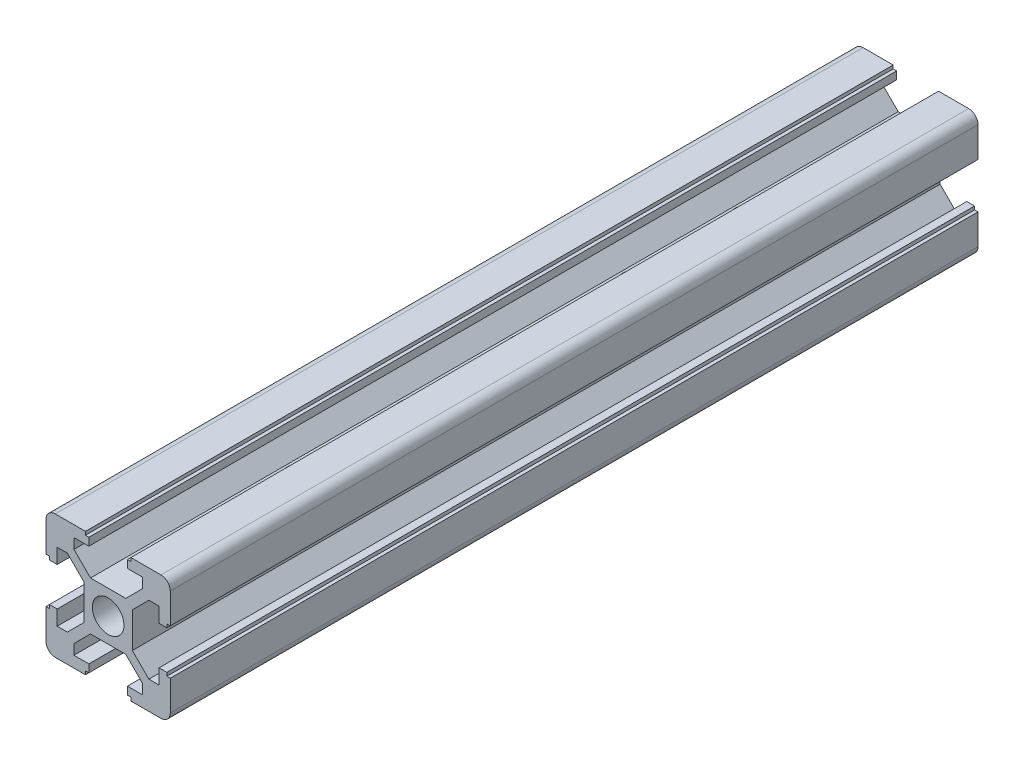
SolidWorks part; units mm, degrees
material "6063-T5"
ref_plane "前视基准面" through (0, 0, 0) normal (0, 0, 1) x (1, 0, 0)
ref_plane "上视基准面" through (0, 0, 0) normal (0, 1, 0) x (1, 0, 0)
ref_plane "右视基准面" through (0, 0, 0) normal (1, 0, 0) x (0, 0, -1)
sketch "草图1" plane through (0, 0, 0) normal (0, 0, 1) x (1, 0, 0)
  line L0 (-3.9, 2.8393) -> (-6.5607, 5.5)
  line L1 (-2.8393, 3.9) -> (2.8393, 3.9)
  line L2 (-3.9, 2.8393) -> (-3.9, -2.8393)
  line L3 (-2.8393, -3.9) -> (2.8393, -3.9)
  line L4 (3.9, 2.8393) -> (3.9, -2.8393)
  line L5 (-3.9, 3.9) -> (3.9, -3.9) construction
  line L6 (-3.9, -3.9) -> (3.9, 3.9) construction
  line L7 (-2.8393, 3.9) -> (-5.5, 6.5607)
  line L8 (-5.5, 6.5607) -> (-5.5, 8.2)
  line L9 (-5.5, 8.2) -> (-3.1, 8.2)
  line L10 (-3.1, 8.2) -> (-3.1, 9.45)
  line L11 (-3.1, 9.45) -> (-3.65, 9.45)
  line L12 (-3.65, 9.45) -> (-3.65, 10)
  line L13 (-3.65, 10) -> (-8.5, 10)
  line L14 (-6.5607, 5.5) -> (-8.2, 5.5)
  line L15 (-10, 3.65) -> (-10, 8.5)
  line L16 (-9.45, 3.65) -> (-10, 3.65)
  line L17 (-9.45, 3.1) -> (-9.45, 3.65)
  line L18 (-8.2, 3.1) -> (-9.45, 3.1)
  line L19 (-8.2, 5.5) -> (-8.2, 3.1)
  line L20 (2.8393, 3.9) -> (5.5, 6.5607)
  line L21 (3.9, 2.8393) -> (6.5607, 5.5)
  line L22 (6.5607, 5.5) -> (8.2, 5.5)
  line L23 (8.2, 5.5) -> (8.2, 3.1)
  line L24 (8.2, 3.1) -> (9.45, 3.1)
  line L25 (9.45, 3.1) -> (9.45, 3.65)
  line L26 (9.45, 3.65) -> (10, 3.65)
  line L27 (10, 3.65) -> (10, 8.5)
  line L28 (5.5, 6.5607) -> (5.5, 8.2)
  line L29 (3.65, 10) -> (8.5, 10)
  line L30 (3.65, 9.45) -> (3.65, 10)
  line L31 (3.1, 9.45) -> (3.65, 9.45)
  line L32 (3.1, 8.2) -> (3.1, 9.45)
  line L33 (5.5, 8.2) -> (3.1, 8.2)
  line L34 (3.9, -2.8393) -> (6.5607, -5.5)
  line L35 (2.8393, -3.9) -> (5.5, -6.5607)
  line L36 (5.5, -6.5607) -> (5.5, -8.2)
  line L37 (5.5, -8.2) -> (3.1, -8.2)
  line L38 (3.1, -8.2) -> (3.1, -9.45)
  line L39 (3.1, -9.45) -> (3.65, -9.45)
  line L40 (3.65, -9.45) -> (3.65, -10)
  line L41 (3.65, -10) -> (8.5, -10)
  line L42 (6.5607, -5.5) -> (8.2, -5.5)
  line L43 (10, -3.65) -> (10, -8.5)
  line L44 (9.45, -3.65) -> (10, -3.65)
  line L45 (9.45, -3.1) -> (9.45, -3.65)
  line L46 (8.2, -3.1) -> (9.45, -3.1)
  line L47 (8.2, -5.5) -> (8.2, -3.1)
  line L48 (-2.8393, -3.9) -> (-5.5, -6.5607)
  line L49 (-3.9, -2.8393) -> (-6.5607, -5.5)
  line L50 (-6.5607, -5.5) -> (-8.2, -5.5)
  line L51 (-8.2, -5.5) -> (-8.2, -3.1)
  line L52 (-8.2, -3.1) -> (-9.45, -3.1)
  line L53 (-9.45, -3.1) -> (-9.45, -3.65)
  line L54 (-9.45, -3.65) -> (-10, -3.65)
  line L55 (-10, -3.65) -> (-10, -8.5)
  line L56 (-5.5, -6.5607) -> (-5.5, -8.2)
  line L57 (-3.65, -10) -> (-8.5, -10)
  line L58 (-3.65, -9.45) -> (-3.65, -10)
  line L59 (-3.1, -9.45) -> (-3.65, -9.45)
  line L60 (-3.1, -8.2) -> (-3.1, -9.45)
  line L61 (-5.5, -8.2) -> (-3.1, -8.2)
  circle A0 centre (0, 0) radius 2.55
  arc A1 (-8.5, 10) -> (-10, 8.5) centre (-8.5, 8.5) ccw
  arc A2 (10, 8.5) -> (8.5, 10) centre (8.5, 8.5) ccw
  arc A3 (8.5, -10) -> (10, -8.5) centre (8.5, -8.5) ccw
  arc A4 (-10, -8.5) -> (-8.5, -10) centre (-8.5, -8.5) ccw
  point P74 (0, 0)
  dimension "D1" = 5.1
  dimension "D8" = 1.5
  dimension "D2" = 7.8
  dimension "D3" = 1.5
  dimension "D4" = 3.1
  dimension "D5" = 0.55
  dimension "D6" = 1.8
  dimension "D7" = 5.5
  dimension "D9" = 3.9
extrude "凸台-拉伸1" add sketch "草图1" along normal blind 130
sketch "草图2" plane through (0, -3.9, 0) normal (0, -1, 0) x (1, 0, 0)
  line L0 (0, 80.6187) -> (0, 52.2824) construction
  circle A0 centre (0, 98.6187) radius 2.5
  circle A1 centre (0, 80.6187) radius 2.5
  circle A2 centre (0, 62.6187) radius 2.5
  circle A3 centre (0, 44.6187) radius 2.5
  circle A4 centre (0, 26.6187) radius 2.5
  dimension "D1" = 4
extrude "切除-拉伸1" cut sketch "草图2" against normal blind 20
